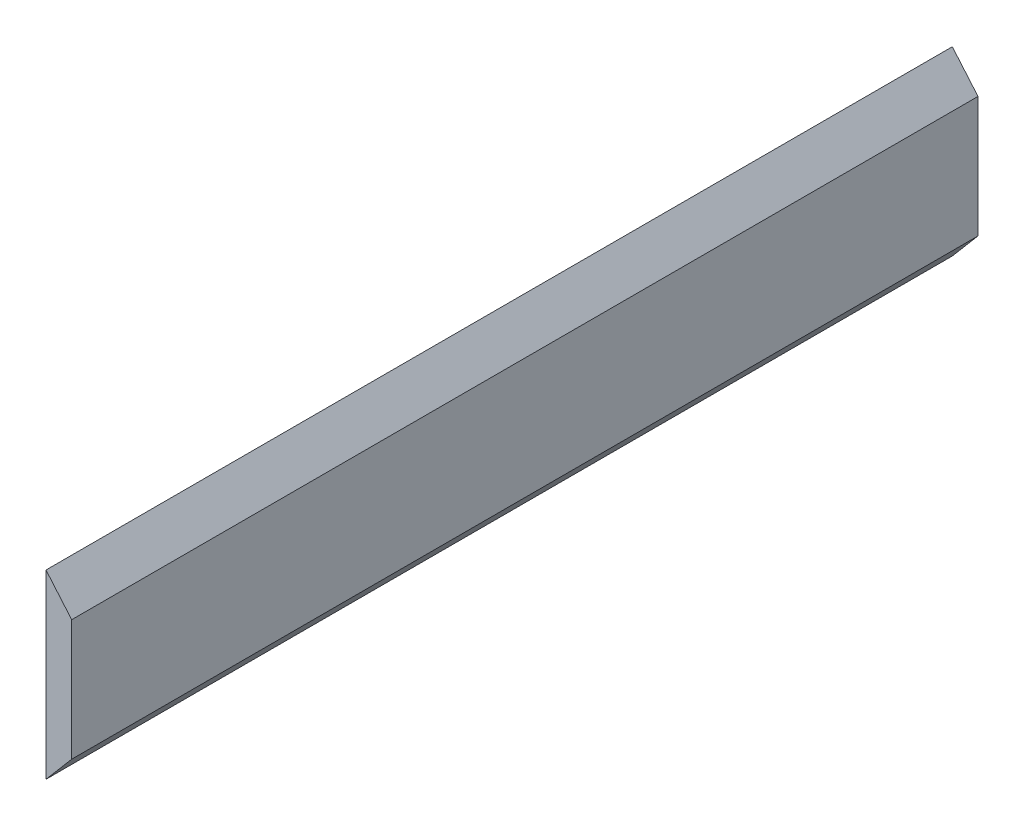
SolidWorks part; units mm, degrees
ref_plane "Front Plane" through (0, 0, 0) normal (0, 0, 1) x (1, 0, 0)
ref_plane "Top Plane" through (0, 0, 0) normal (0, 1, 0) x (1, 0, 0)
ref_plane "Right Plane" through (0, 0, 0) normal (1, 0, 0) x (0, 0, -1)
sketch "Sketch2" plane through (0, 0, 0) normal (0, 0, 1) x (1, 0, 0)
  line L0 (-148, 5) -> (-148, 250) construction
  line L1 (-131, 85) -> (-148, 65) construction
  line L2 (-131, 165) -> (-131, 85) construction
  line L3 (-148, 185) -> (-131, 165) construction
  line L4 (-148, 65) -> (-148, 185)
  line L5 (-131, 85) -> (-148, 65)
  line L6 (-131, 165) -> (-131, 85)
  line L7 (-148, 185) -> (-131, 165)
extrude "Boss-Extrude1" add sketch "Sketch2" along normal up to surface (600 mm away)
